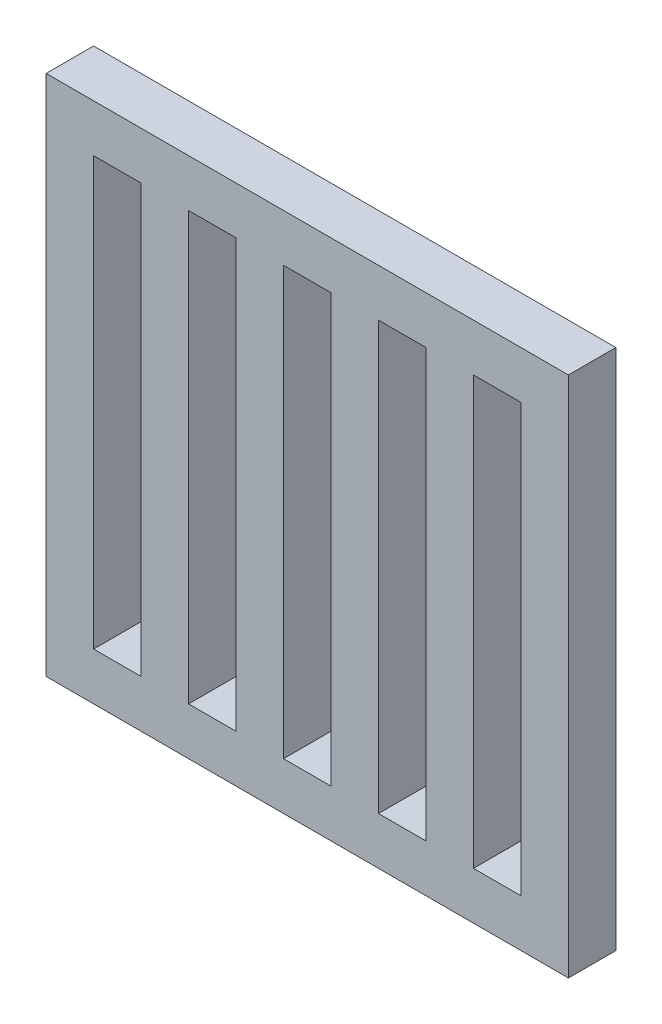
SolidWorks part; units mm, degrees
material "Бальса"
ref_plane "Спереди" through (0, 0, 0) normal (0, 0, 1) x (1, 0, 0)
ref_plane "Сверху" through (0, 0, 0) normal (0, 1, 0) x (1, 0, 0)
ref_plane "Справа" through (0, 0, 0) normal (1, 0, 0) x (0, 0, -1)
sketch "Эскиз1" plane through (0, 0, 0) normal (0, 0, 1) x (1, 0, 0)
  line L1 (0, 0) -> (550, 0)
  line L2 (0, 0) -> (0, -550)
  line L3 (0, -550) -> (550, -550)
  line L4 (550, 0) -> (550, -550)
  dimension "D1" = 550
  dimension "D2" = 550
extrude "Бобышка-Вытянуть1" add sketch "Эскиз1" along normal blind 50
sketch "Эскиз2" plane through (0, 0, 50) normal (0, 0, 1) x (1, 0, 0)
  line L0 (0, -50) -> (50, -50) construction
  line L3 (50, -50) -> (50, 0) construction
  line L4 (50, -100) -> (50, -150) construction
  line L5 (550, 0) -> (0, 0) construction
  line L6 (0, -550) -> (550, -550) construction
  line L7 (500, 0) -> (500, -550) construction
  line L8 (50, -50) -> (500, -50)
  line L9 (50, -50) -> (50, -100)
  line L10 (50, -100) -> (500, -100)
  line L11 (500, -50) -> (500, -100)
  line L12 (50, -150) -> (500, -150)
  line L13 (50, -150) -> (50, -200)
  line L14 (50, -200) -> (500, -200)
  line L15 (500, -150) -> (500, -200)
  line L16 (50, -250) -> (500, -250)
  line L17 (50, -250) -> (50, -300)
  line L18 (50, -300) -> (500, -300)
  line L19 (500, -250) -> (500, -300)
  line L20 (50, -350) -> (500, -350)
  line L21 (50, -350) -> (50, -400)
  line L22 (50, -400) -> (500, -400)
  line L23 (500, -350) -> (500, -400)
  line L24 (50, -450) -> (500, -450)
  line L25 (50, -450) -> (50, -500)
  line L26 (50, -500) -> (500, -500)
  line L27 (500, -450) -> (500, -500)
  line L28 (50, -200) -> (50, -250) construction
  line L29 (50, -300) -> (50, -350) construction
  line L30 (50, -400) -> (50, -450) construction
  line L31 (50, -500) -> (50, -550) construction
  line L32 (0, 0) -> (0, -550) construction
  line L33 (500, -50) -> (550, -50) construction
  line L34 (550, -550) -> (550, 0) construction
extrude "Вырез-Вытянуть1" [suppressed] cut sketch "Эскиз2" against normal through all
sketch "Эскиз4" plane through (0, 0, 50) normal (0, 0, 1) x (1, 0, 0)
  line L0 (0, -50) -> (50, -50) construction
  line L1 (50, -50) -> (100, -50)
  line L2 (50, -50) -> (50, -500)
  line L3 (50, -500) -> (100, -500)
  line L4 (100, -50) -> (100, -500)
  line L5 (150, -50) -> (200, -50)
  line L6 (150, -50) -> (150, -500)
  line L7 (150, -500) -> (200, -500)
  line L8 (200, -50) -> (200, -500)
  line L9 (250, -50) -> (300, -50)
  line L10 (250, -50) -> (250, -500)
  line L11 (250, -500) -> (300, -500)
  line L12 (300, -50) -> (300, -500)
  line L13 (350, -50) -> (400, -50)
  line L14 (350, -50) -> (350, -500)
  line L15 (350, -500) -> (400, -500)
  line L16 (400, -50) -> (400, -500)
  line L17 (450, -50) -> (500, -50)
  line L18 (450, -50) -> (450, -500)
  line L19 (450, -500) -> (500, -500)
  line L20 (500, -50) -> (500, -500)
  line L21 (0, 0) -> (0, -550) construction
  line L22 (50, -50) -> (50, 0) construction
  line L23 (550, 0) -> (0, 0) construction
  line L24 (100, -50) -> (150, -50) construction
  line L25 (200, -50) -> (250, -50) construction
  line L26 (300, -50) -> (350, -50) construction
  line L27 (400, -50) -> (450, -50) construction
  line L28 (500, -50) -> (550, -50) construction
  line L30 (50, -500) -> (50, -550) construction
  line L31 (0, -550) -> (550, -550) construction
  line L36 (550, -550) -> (550, 0) construction
extrude "Вырез-Вытянуть2" cut sketch "Эскиз4" against normal through all
